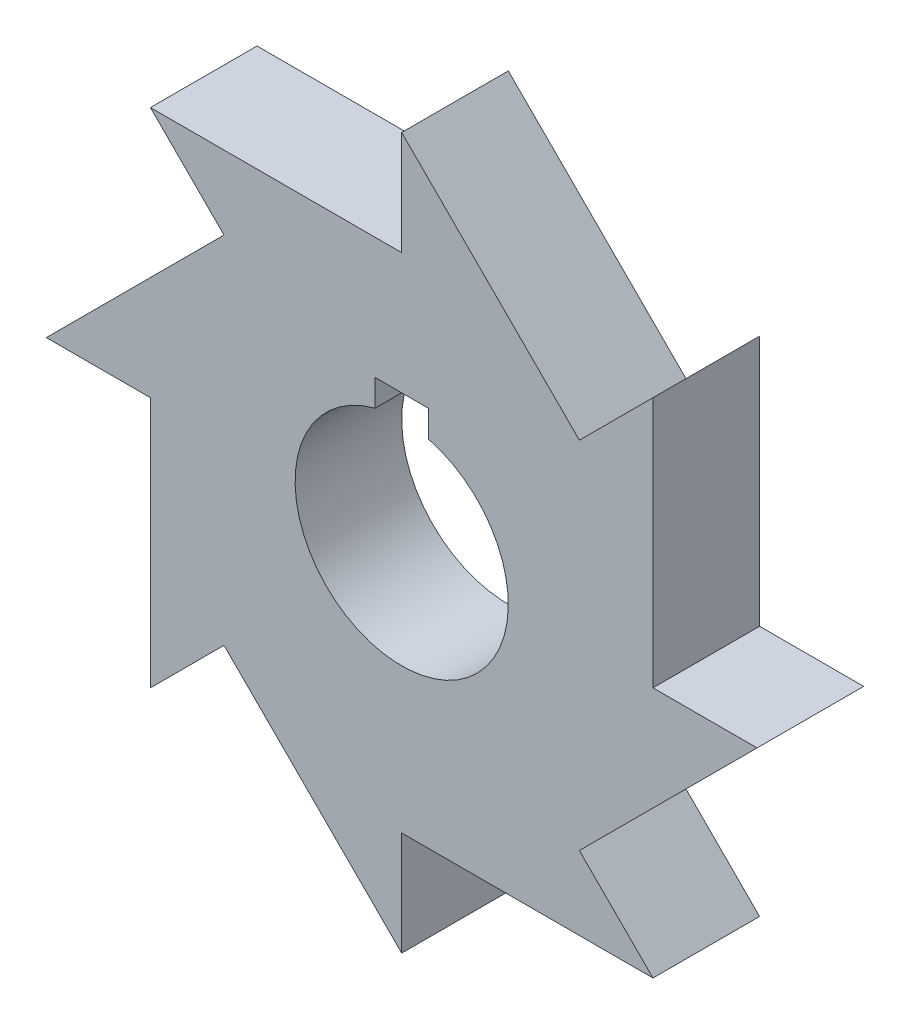
SolidWorks part; units mm, degrees
ref_plane "Front Plane" through (0, 0, 0) normal (0, 0, 1) x (1, 0, 0)
ref_plane "Top Plane" through (0, 0, 0) normal (0, 1, 0) x (1, 0, 0)
ref_plane "Right Plane" through (0, 0, 0) normal (1, 0, 0) x (0, 0, -1)
sketch "Sketch1" plane through (0, 0, 0) normal (0, 0, 1) x (1, 0, 0)
  line L0 (-74.2173, 0) -> (82.1583, 0) construction
  line L1 (0, 71.7764) -> (0, -72.568) construction
  line L2 (-55.2356, -55.2356) -> (0, 0) construction
  line L3 (-4.7625, 23.2076) -> (4.7625, 23.2076)
  line L4 (-4.7625, 23.2076) -> (-4.7625, 18.4451)
  line L6 (4.7625, 23.2076) -> (4.7625, 18.4451)
  line L7 (0, 0) -> (57.796, 57.796) construction
  line L8 (56.6897, -56.6897) -> (0, 0) construction
  line L9 (0, 0) -> (-49.4615, 49.4615) construction
  line L10 (0, 63.5) -> (31.75, 31.75)
  line L11 (31.75, 31.75) -> (44.9013, 44.9013)
  line L12 (44.9013, 44.9013) -> (44.9013, 0)
  line L13 (44.9013, 0) -> (63.5, 0)
  line L14 (63.5, 0) -> (31.75, -31.75)
  line L15 (31.75, -31.75) -> (44.9013, -44.9013)
  line L16 (44.9013, -44.9013) -> (0, -44.9013)
  line L17 (0, -44.9013) -> (0, -63.5)
  line L18 (0, -63.5) -> (-31.75, -31.75)
  line L19 (-31.75, -31.75) -> (-44.9013, -44.9013)
  line L20 (-44.9013, -44.9013) -> (-44.9013, 0)
  line L21 (-44.9013, 0) -> (-63.5, 0)
  line L22 (-63.5, 0) -> (-31.75, 31.75)
  line L23 (-31.75, 31.75) -> (-44.9013, 44.9013)
  line L24 (-44.9013, 44.9013) -> (0, 44.9013)
  line L25 (0, 44.9013) -> (0, 63.5)
  arc A0 (-4.7625, 18.4451) -> (4.7625, 18.4451) centre (0, 0) ccw
  point P3 (-22.4506, 44.9013)
  point P8 (0, 19.05)
  point P33 (-67.691, 60.3758)
  dimension "D1" = 38.1
  dimension "D2" = 44.9013
  dimension "D3" = 9.525
  dimension "D4" = 4.7625
  dimension "D5" = 23.2076
  dimension "D6" = 45
  dimension "D7" = 45
  dimension "D8" = 90
  dimension "D9" = 44.9013
  dimension "D10" = 44.9013
  dimension "D11" = 44.9013
  dimension "D12" = 44.9013
  dimension "D13" = 89.8026
  dimension "D14" = 89.8026
  dimension "D15" = 60.7763
extrude "Boss-Extrude1" add sketch "Sketch1" along normal mid plane 19.05
